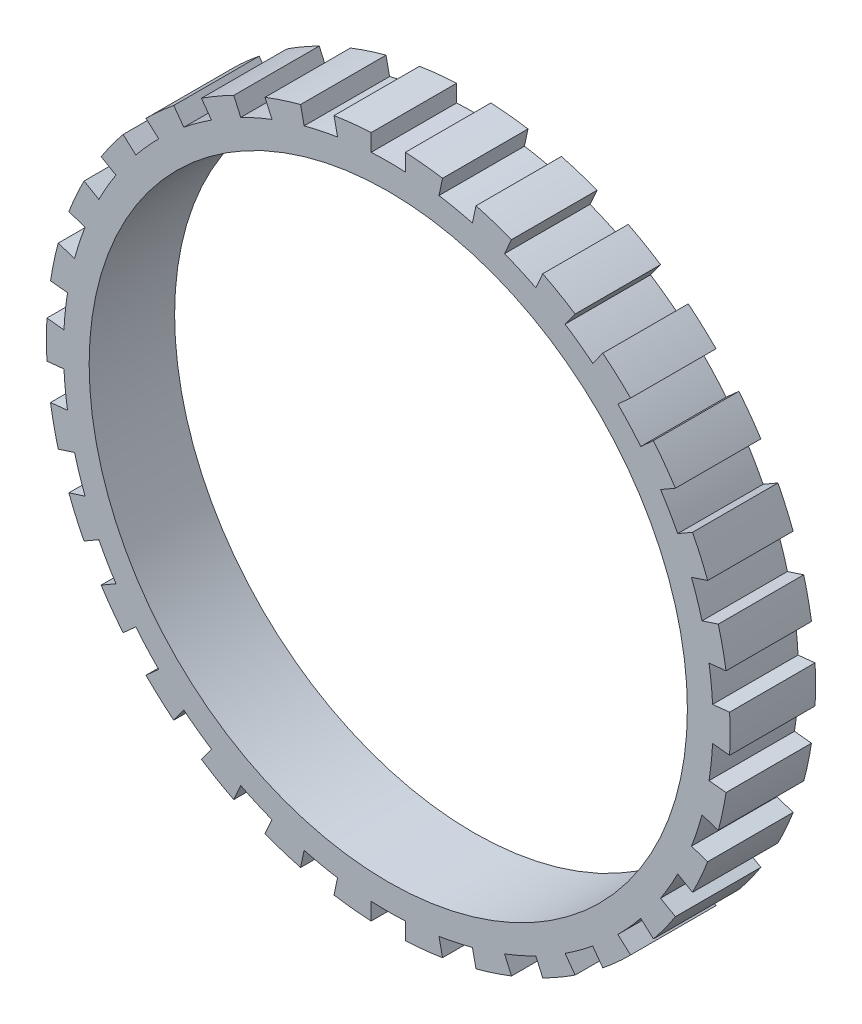
SolidWorks part; units mm, degrees
material "Rubber"
ref_plane "Front Plane" through (0, 0, 0) normal (0, 0, 1) x (1, 0, 0)
ref_plane "Top Plane" through (0, 0, 0) normal (0, 1, 0) x (1, 0, 0)
ref_plane "Right Plane" through (0, 0, 0) normal (1, 0, 0) x (0, 0, -1)
sketch "Sketch1" plane through (0, 0, 0) normal (0, 0, 1) x (1, 0, 0)
  circle A0 centre (0, 0) radius 35
  circle A1 centre (0, 0) radius 40
extrude "Boss-Extrude1" add sketch "Sketch1" along normal blind 10
sketch "Sketch4" plane through (0, 0, 0) normal (0, 0, 1) x (1, 0, 0)
  line L0 (0, 38) -> (0, 40) construction
  line L1 (2, 37.9473) -> (2, 39.95)
  line L2 (-2, 37.9473) -> (-2, 39.95)
  line L3 (-2, 0) -> (-2, 40) construction
  line L4 (0, 0) -> (0, 40) construction
  line L5 (2, 0) -> (2, 40) construction
  arc A0 (2, 39.95) -> (-2, 39.95) centre (0, 0) ccw
  arc A1 (2, 37.9473) -> (-2, 37.9473) centre (0, 0) ccw
  dimension "D1" = 2
  dimension "D2" = 2
extrude "Cut-Extrude5" cut sketch "Sketch4" along normal up to surface (10 mm away) up to face at (40, 0, 10)
pattern_circular "CirPattern2" count 30 over 360 about axis through (0, 0, 0) along (0, 0, 1) of "Cut-Extrude5"
